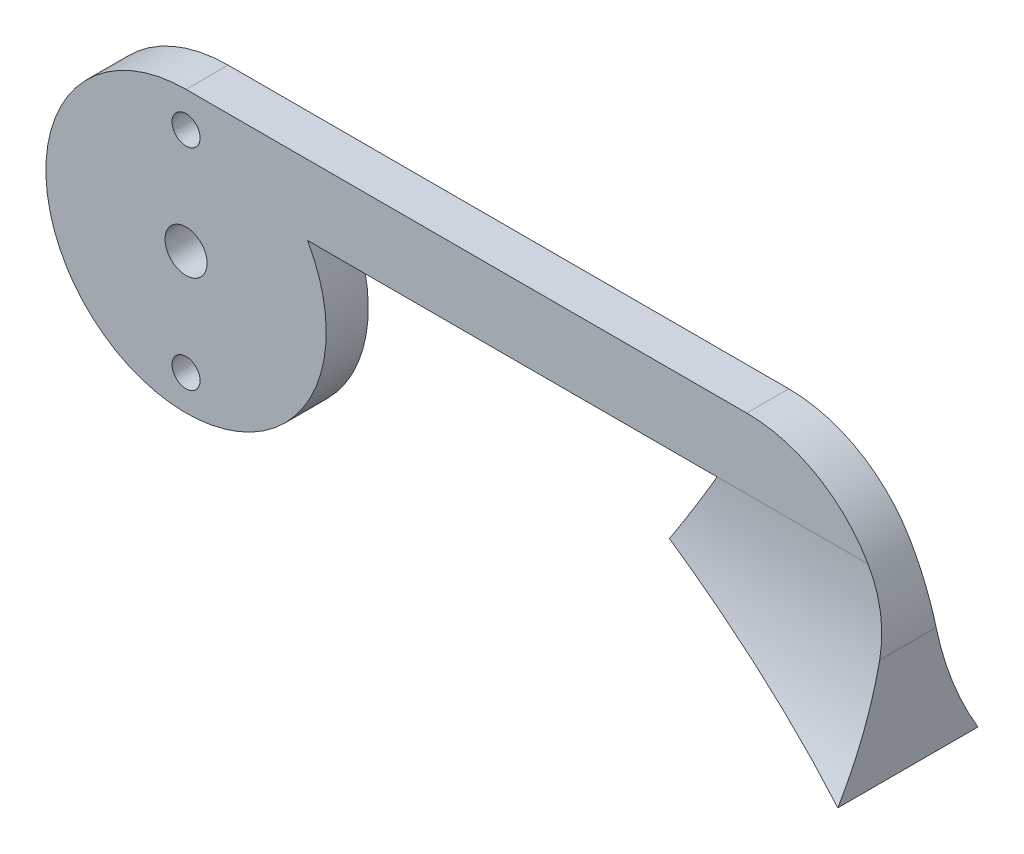
SolidWorks part; units mm, degrees
ref_plane "Front Plane" through (0, 0, 0) normal (0, 0, 1) x (1, 0, 0)
ref_plane "Top Plane" through (0, 0, 0) normal (0, 1, 0) x (1, 0, 0)
ref_plane "Right Plane" through (0, 0, 0) normal (1, 0, 0) x (0, 0, -1)
sketch "Sketch1" plane through (0, 0, 0) normal (0, 0, 1) x (1, 0, 0)
  line L0 (0, 10) -> (40, 10)
  line L1 (8.6603, 5) -> (37.8868, 5)
  line L2 (37.8868, 5) -> (35, 0)
  line L3 (35, 0) -> (50, 0)
  arc A0 (0, 10) -> (8.6603, 5) centre (0, 0) ccw
  arc A1 (40, 10) -> (50, 0) centre (40, 0) cw
  circle A2 centre (0, 0) radius 1.5
  dimension "D1" = 50
  dimension "D2" = 20
  dimension "D4" = 60
  dimension "D7" = 3
  dimension "D3" = 15
  dimension "D5" = 5
  dimension "D6" = 5
extrude "Boss-Extrude1" add sketch "Sketch1" along normal mid plane 3
sketch "Sketch2" plane through (0, 0, 0) normal (0, 0, 1) x (1, 0, 0)
  line L0 (37.8868, 5) -> (37.8868, 10)
  line L1 (40, 10) -> (0, 10) construction
  line L2 (37.8868, 10) -> (40, 10)
  line L4 (35, 0) -> (37.8868, 5)
  line L5 (50, 0) -> (50, -7.6429)
  line L6 (50, -7.6429) -> (35, 0)
  arc A1 (40, 10) -> (50, 0) centre (40, 0) cw
  dimension "D1" = 27
extrude "Boss-Extrude2" add sketch "Sketch2" along normal mid plane 10
sketch "Sketch3" plane through (37.8868, 0, 0) normal (-1, 0, 0) x (0, 0, 1)
  line L2 (-1.5, 10) -> (-1.5, 5)
  line L7 (-5, -7.6429) -> (5, -7.6429)
  line L8 (5, -7.6429) -> (-5, -7.6429) construction
  line L9 (0, -7.6429) -> (0, 10) construction
  line L10 (1.5, 10) -> (-1.5, 10) construction
  line L11 (-1.5, 10) -> (1.5, 10)
  line L12 (1.5, 10) -> (1.5, 5)
  arc A2 (-1.5, 5) -> (-5, -7.6429) centre (-26.0846, 5) cw
  arc A3 (1.5, 5) -> (5, -7.6429) centre (26.0846, 5) ccw
extrude "Cut-Extrude1" cut sketch "Sketch3" against normal through all and the other way up to surface flip side to cut
sketch "Sketch4" plane through (0, 0, -1.5) normal (0, 0, -1) x (-1, 0, 0)
  line L0 (0, 7.5) -> (0, -7.5) construction
  circle A0 centre (0, 7.5) radius 1
  circle A1 centre (0, -7.5) radius 1
  point P4 (0, 0)
  dimension "D1" = 15
  dimension "D2" = 2
extrude "Cut-Extrude2" cut sketch "Sketch4" against normal through all
